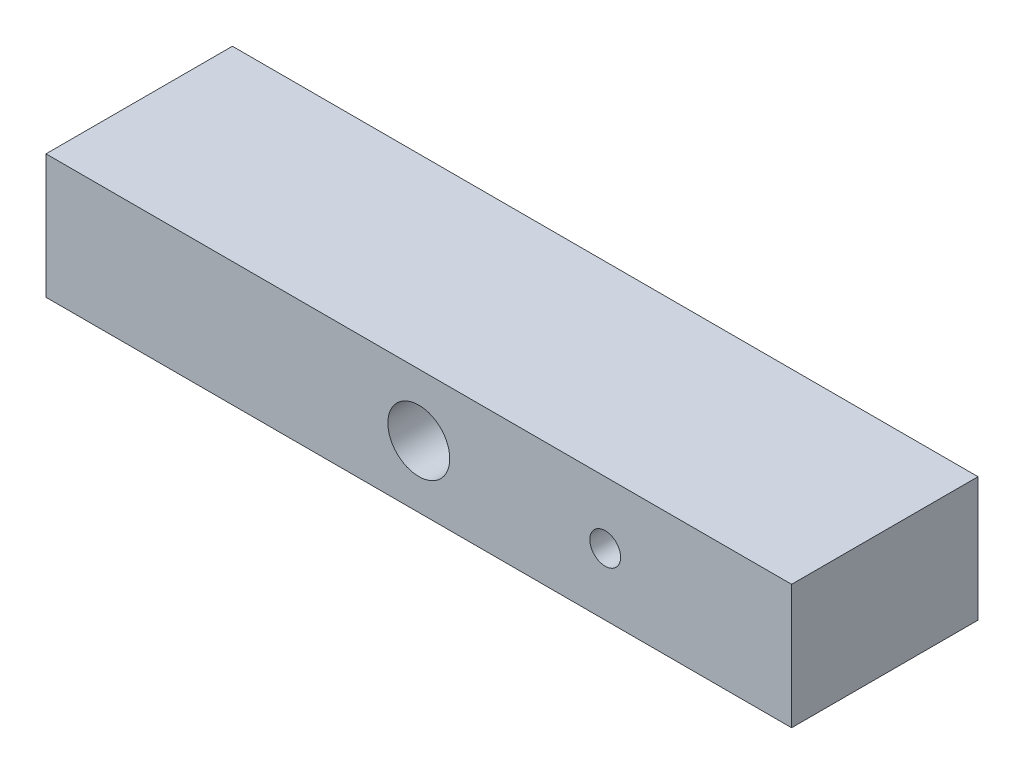
SolidWorks part; units mm, degrees
ref_plane "Front Plane" through (0, 0, 0) normal (0, 0, 1) x (1, 0, 0)
ref_plane "Top Plane" through (0, 0, 0) normal (0, 1, 0) x (1, 0, 0)
ref_plane "Right Plane" through (0, 0, 0) normal (1, 0, 0) x (0, 0, -1)
sketch "Sketch1" plane through (0, 0, 0) normal (0, 0, 1) x (1, 0, 0)
  line L1 (-42.9025, 12.7) -> (33.2975, 12.7)
  line L2 (-42.9025, 12.7) -> (-42.9025, 0)
  line L3 (-42.9025, 0) -> (33.2975, 0)
  line L4 (33.2975, 12.7) -> (33.2975, 0)
  dimension "D1" = 12.7
  dimension "D2" = 76.2
extrude "Boss-Extrude1" add sketch "Sketch1" along normal blind 19.05
sketch "Sketch2" plane through (0, 0, 19.05) normal (0, 0, 1) x (1, 0, 0)
  line L0 (-42.9025, 12.7) -> (-42.9025, 0) construction
  line L1 (33.2975, 12.7) -> (-42.9025, 12.7) construction
  circle A0 centre (-4.8025, 6.35) radius 3.1623
  circle A1 centre (14.2475, 6.35) radius 1.5748
  point P6 (-4.8025, 12.7)
  dimension "D4" = 6.3246
  dimension "D5" = 3.1496
  dimension "D1" = 38.1
  dimension "D2" = 19.05
  dimension "D3" = 6.35
extrude "Cut-Extrude1" cut sketch "Sketch2" against normal blind 19.05
